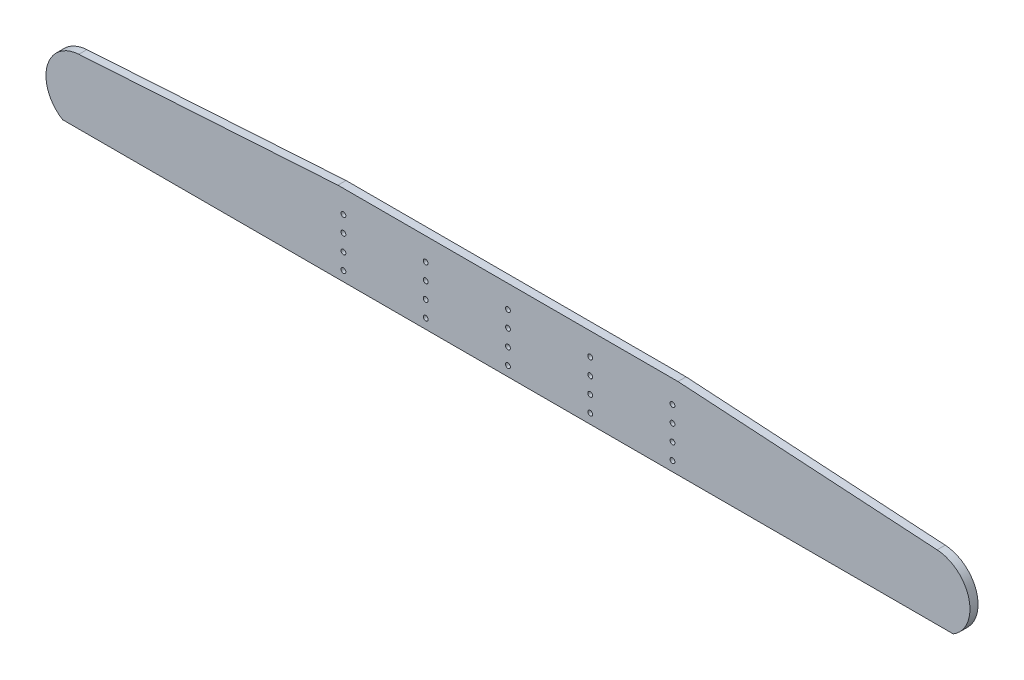
SolidWorks part; units mm, degrees
ref_plane "Front Plane" through (0, 0, 0) normal (0, 0, 1) x (1, 0, 0)
ref_plane "Top Plane" through (0, 0, 0) normal (0, 1, 0) x (1, 0, 0)
ref_plane "Right Plane" through (0, 0, 0) normal (1, 0, 0) x (0, 0, -1)
sketch "Sketch3" plane through (0, 0, 0) normal (0, 0, 1) x (1, 0, 0)
  line L0 (105, -25) -> (275, -25)
  line L1 (-105, 25) -> (105, 25)
  line L2 (-105, 25) -> (-105, -25)
  line L3 (-105, -25) -> (105, -25)
  line L4 (105, 25) -> (105, -25)
  line L5 (-105, 25) -> (105, -25) construction
  line L6 (-105, -25) -> (105, 25) construction
  line L7 (105, 25) -> (265, 15)
  line L8 (265, 15) -> (265, -25)
  line L9 (0, 0) -> (0, 149.1164) construction
  line L10 (-265, 15) -> (-265, -25)
  line L11 (-105, -25) -> (-275, -25)
  line L12 (-105, 25) -> (-265, 15)
  arc A0 (265, 15) -> (275, -25) centre (263.6508, -6.5873) cw
  arc A1 (-265, 15) -> (-275, -25) centre (-263.6508, -6.5873) ccw
  point P0 (0, 0)
  dimension "D1" = 210
  dimension "D2" = 50
  dimension "D3" = 170
  dimension "D4" = 160
  dimension "D5" = 10
extrude "Boss-Extrude1" add sketch "Sketch3" along normal blind 5 contours L2 L12 L10 L11 | L10 A1 L11 | L4 L1 L2 L3 | L8 L7 L4 L0 | A0 L8 L0
sketch "Sketch8" plane through (0, 0, 5) normal (0, 0, 1) x (1, 0, 0)
  line L0 (-265, 15) -> (-265, -25) construction
  line L1 (-105, 25) -> (-265, 15) construction
  line L2 (-105, -25) -> (-275, -25) construction
  line L3 (265, 15) -> (265, -25) construction
  line L4 (105, 25) -> (265, 15) construction
  line L5 (105, -25) -> (275, -25) construction
  line L6 (-105, 25) -> (-105, -25) construction
  line L7 (-105, -25) -> (105, -25) construction
  line L8 (-105, 25) -> (105, 25) construction
  line L9 (105, 25) -> (105, -25) construction
  line L10 (-265, 15) -> (-265, -25)
  line L11 (-105, 25) -> (-265, 15)
  line L12 (-105, -25) -> (-275, -25)
  line L13 (265, 15) -> (265, -25)
  line L14 (105, 25) -> (265, 15)
  line L15 (105, -25) -> (275, -25)
  line L16 (-105, 25) -> (-105, -25)
  line L17 (-105, -25) -> (105, -25)
  line L18 (-105, 25) -> (105, 25)
  line L19 (105, 25) -> (105, -25)
  arc A0 (-265, 15) -> (-275, -25) centre (-263.6508, -6.5873) ccw construction
  arc A1 (275, -25) -> (265, 15) centre (263.6508, -6.5873) ccw construction
  arc A2 (-265, 15) -> (-275, -25) centre (-263.6508, -6.5873) ccw
  arc A3 (275, -25) -> (265, 15) centre (263.6508, -6.5873) ccw
  circle A4 centre (0, 11) radius 1.5
  circle A5 centre (0, 1) radius 1.5
  circle A6 centre (0, -9) radius 1.5
  circle A7 centre (0, -19) radius 1.5
  circle A8 centre (50.8, 11) radius 1.5
  circle A9 centre (50.8, -9) radius 1.5
  circle A10 centre (50.8, 1) radius 1.5
  circle A11 centre (50.8, -19) radius 1.5
  circle A12 centre (101.6, 11) radius 1.5
  circle A13 centre (101.6, -9) radius 1.5
  circle A14 centre (101.6, 1) radius 1.5
  circle A15 centre (101.6, -19) radius 1.5
  circle A16 centre (-50.8, 11) radius 1.5
  circle A17 centre (-50.8, 1) radius 1.5
  circle A18 centre (-50.8, -9) radius 1.5
  circle A19 centre (-50.8, -19) radius 1.5
  circle A20 centre (-101.6, 11) radius 1.5
  circle A21 centre (-101.6, 1) radius 1.5
  circle A22 centre (-101.6, -9) radius 1.5
  circle A23 centre (-101.6, -19) radius 1.5
  dimension "D1" = 14
  dimension "D2" = 10
  dimension "D3" = 10
  dimension "D4" = 10
  dimension "D5" = 3
  dimension "D6" = 3
extrude "Cut-Extrude1" cut sketch "Sketch8" against normal blind 5 contours A20 | A21 | A22 | A23 | A5 | A6 | A7 | A4 | A16 | A17 | A18 | A19 | A11 | A9 | A10 | A8 | A12 | A14 | A13 | A15
